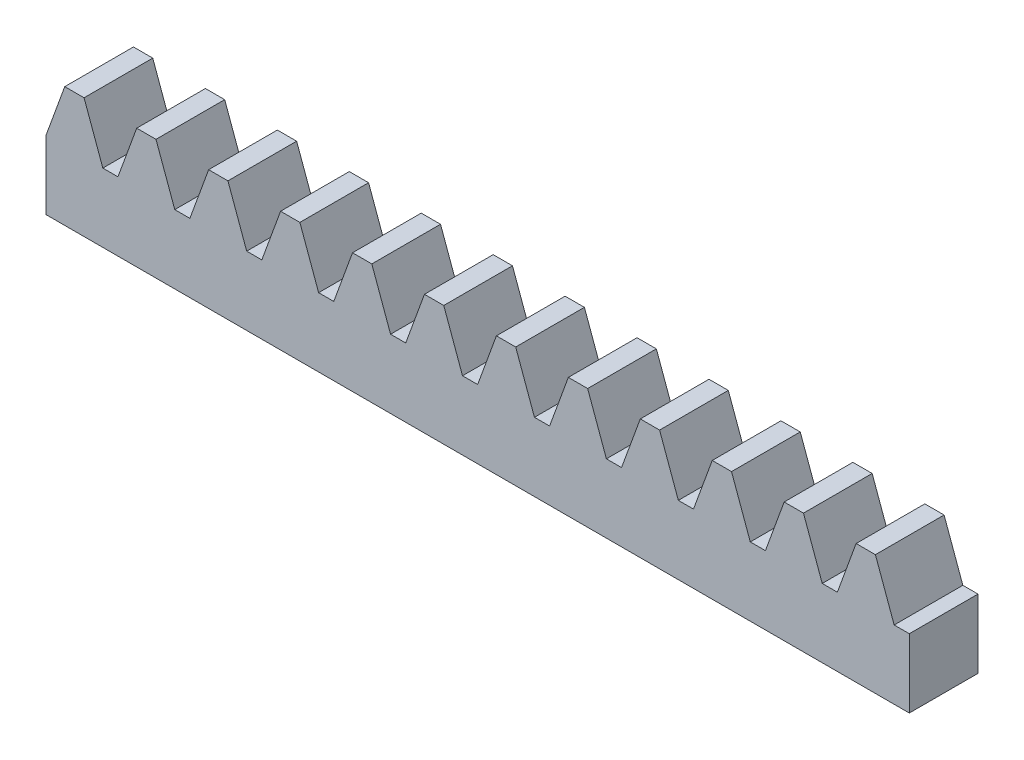
SolidWorks part; units mm, degrees
ref_plane "前视基准面" through (0, 0, 0) normal (0, 0, 1) x (1, 0, 0)
ref_plane "上视基准面" through (0, 0, 0) normal (0, 1, 0) x (1, 0, 0)
ref_plane "右视基准面" through (0, 0, 0) normal (1, 0, 0) x (0, 0, -1)
sketch "草图1" plane through (0, 0, 0) normal (0, 0, 1) x (1, 0, 0)
  line L1 (0, 0) -> (75.3982, 0)
  line L2 (0, 0) -> (0, -6)
  line L3 (0, -6) -> (75.3982, -6)
  line L4 (75.3982, 0) -> (75.3982, -6)
  dimension "D1" = 6
  dimension "L" = 75.3982
extrude "拉伸1" add sketch "草图1" along normal blind 6
sketch "草图2" plane through (0, 0, 6) normal (0, 0, 1) x (1, 0, 0)
  line L0 (0, 0) -> (1.6379, 4.5)
  line L1 (1.6379, 4.5) -> (3.3236, 4.5)
  line L2 (3.3236, 4.5) -> (4.9614, 0)
  line L3 (75.3982, 0) -> (0, 0) construction
  line L4 (0, 0) -> (4.9614, 0)
  line L5 (0.9099, 2.5) -> (4.0515, 2.5) construction
  dimension "D2" = 70
  dimension "alpha" = 110
  dimension "ha" = 2
  dimension "hf" = 2.5
  dimension "S" = 3.1416
extrude "拉伸2" add sketch "草图2" against normal up to surface (6 mm away) up to face at (37.6991, -3, 0)
pattern_linear "阵列(线性)1" count 12 spacing 6.2832 along (1, 0, 0) of "拉伸2"
sketch "草图3" plane through (0, 0, 0) normal (0, 0, -1) x (-1, 0, 0)
  line L0 (-73.2575, 2.25) -> (-0.8189, 2.25) construction
  line L1 (-72.4386, 4.5) -> (-74.0765, 0) construction
  line L2 (0, 0) -> (-1.6379, 4.5) construction
equation "\"d\"=\"S@草图2\" * 2"
equation "\"z\"= int(  \"L@草图1\" / (  \"S@草图2\" * 2 ) + 0.5 )"
